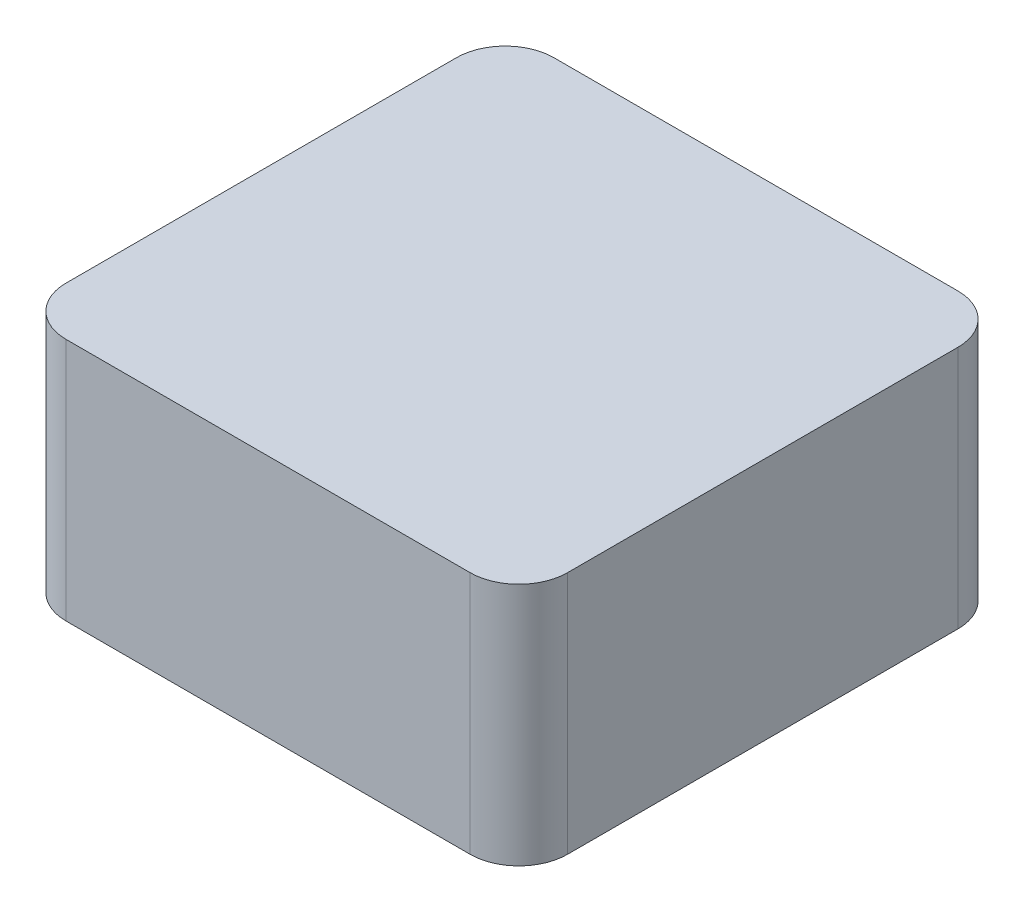
SolidWorks part; units mm, degrees
ref_plane "Front Plane" through (0, 0, 0) normal (0, 0, 1) x (1, 0, 0)
ref_plane "Top Plane" through (0, 0, 0) normal (0, 1, 0) x (1, 0, 0)
ref_plane "Right Plane" through (0, 0, 0) normal (1, 0, 0) x (0, 0, -1)
sketch "Sketch1" plane through (0, 0, 0) normal (0, 1, 0) x (1, 0, 0)
  line L1 (6.5278, -6.35) -> (-6.5278, -6.35)
  line L2 (6.5278, -6.35) -> (6.5278, 6.35)
  line L3 (6.5278, 6.35) -> (-6.5278, 6.35)
  line L4 (-6.5278, -6.35) -> (-6.5278, 6.35)
  line L5 (0, 6.35) -> (0, -6.35) construction
  line L6 (6.5278, 0) -> (-6.5278, 0) construction
  point P0 (0, 0)
  dimension "D1" = 12.7
  dimension "D2" = 13.0556
extrude "Boss-Extrude1" add sketch "Sketch1" along normal blind 6.35
fillet "Fillet1" radius 1.27 4 edges at (6.5278, 3.175, 6.35) (6.5278, 3.175, -6.35) (-6.5278, 3.175, -6.35) (-6.5278, 3.175, 6.35)
